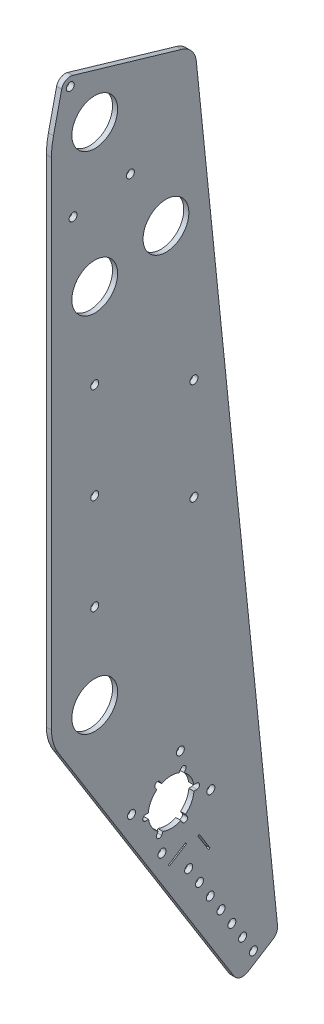
SolidWorks part; units mm, degrees
ref_plane "Front Plane" through (0, 0, 0) normal (0, 0, 1) x (1, 0, 0)
ref_plane "Top Plane" through (0, 0, 0) normal (0, 1, 0) x (1, 0, 0)
ref_plane "Right Plane" through (0, 0, 0) normal (1, 0, 0) x (0, 0, -1)
ref_plane "Plane1" through (1.5875, 0, 0) normal (1, 0, 0) x (0, 0, -1)
sketch "Sketch1" plane through (1.5875, 0, 0) normal (1, 0, 0) x (0, 0, -1)
  line L0 (40.6958, -376.82) -> (41.6603, -378.3635)
  line L1 (52.8023, -377.9745) -> (53.6568, -376.3674)
  line L2 (56.7471, -378.0106) -> (55.8926, -379.6176)
  line L3 (61.8006, -389.0724) -> (63.6196, -389.0088)
  line L4 (63.7417, -392.5067) -> (61.9227, -392.5702)
  line L5 (56.6887, -402.4141) -> (57.6532, -403.9576)
  line L6 (54.685, -405.8123) -> (53.7205, -404.2688)
  line L7 (42.5785, -404.6579) -> (41.724, -406.2649)
  line L8 (38.6337, -404.6217) -> (39.4882, -403.0147)
  line L9 (33.5802, -393.56) -> (31.7612, -393.6235)
  line L10 (31.6391, -390.1256) -> (33.458, -390.0621)
  line L11 (38.6921, -380.2183) -> (37.7276, -378.6748)
  line L12 (45.9843, -424.5347) -> (56.7545, -417.8047)
  line L13 (56.7545, -417.8047) -> (57.2844, -418.6528)
  line L14 (57.2844, -418.6528) -> (46.5142, -425.3827)
  line L15 (46.5142, -425.3827) -> (45.9843, -424.5347)
  line L16 (65.2001, -417.4504) -> (71.93, -428.2206)
  line L17 (71.93, -428.2206) -> (71.082, -428.7505)
  line L18 (71.082, -428.7505) -> (64.352, -417.9803)
  line L19 (64.352, -417.9803) -> (65.2001, -417.4504)
  line L20 (54.3454, 12.1946) -> (-13.7189, 32.1437)
  line L21 (-20.63, 28.0802) -> (-25.7335, 5.5386)
  line L22 (-26.9875, -5.6788) -> (-26.9875, -314.9956)
  line L23 (-22.8867, -329.2968) -> (86.8926, -504.9805)
  line L24 (95.6427, -507.0006) -> (111.1338, -497.3207)
  line L25 (114.0855, -491.2857) -> (63.4067, 1.307)
  circle A0 centre (0, -261.9478) radius 2.5
  circle A1 centre (0, -141.9478) radius 2.5
  circle A2 centre (22.2306, -39.1229) radius 2.5
  circle A3 centre (-13.4937, -44.45) radius 2.5
  arc A4 (37.7276, -378.6748) -> (40.6958, -376.82) centre (39.2117, -377.7474) cw
  arc A5 (41.6603, -378.3635) -> (52.8023, -377.9745) centre (47.6904, -391.3162) cw
  arc A6 (53.6568, -376.3674) -> (56.7471, -378.0106) centre (55.2019, -377.189) cw
  arc A7 (55.8926, -379.6176) -> (61.8006, -389.0724) centre (47.6904, -391.3162) cw
  arc A8 (63.6196, -389.0088) -> (63.7417, -392.5067) centre (63.6806, -390.7578) cw
  arc A9 (61.9227, -392.5702) -> (56.6887, -402.4141) centre (47.6904, -391.3162) cw
  arc A10 (57.6532, -403.9576) -> (54.685, -405.8123) centre (56.1691, -404.8849) cw
  arc A11 (53.7205, -404.2688) -> (42.5785, -404.6579) centre (47.6904, -391.3162) cw
  arc A12 (41.724, -406.2649) -> (38.6337, -404.6217) centre (40.1788, -405.4433) cw
  arc A13 (39.4882, -403.0147) -> (33.5802, -393.56) centre (47.6904, -391.3162) cw
  arc A14 (31.7612, -393.6235) -> (31.6391, -390.1256) centre (31.7001, -391.8746) cw
  arc A15 (33.458, -390.0621) -> (38.6921, -380.2183) centre (47.6904, -391.3162) cw
  circle A16 centre (41.9766, -416.0652) radius 2.5
  circle A17 centre (72.4394, -397.0299) radius 2.5
  circle A18 centre (53.4041, -366.5672) radius 2.5
  circle A19 centre (22.9414, -385.6024) radius 2.5
  circle A20 centre (0, -201.9478) radius 2.5
  circle A21 centre (61.9125, -233.6978) radius 2.5
  circle A22 centre (61.9125, -170.1978) radius 2.5
  circle A23 centre (0, 0) radius 14.2875
  circle A24 centre (0, -88.9) radius 14.2875
  circle A25 centre (0, -314.9956) radius 14.2875
  circle A26 centre (44.4613, -78.2458) radius 14.2875
  circle A27 centre (58.6293, -432.788) radius 2.5
  circle A28 centre (65.3593, -443.5582) radius 2.5
  circle A29 centre (72.0892, -454.3284) radius 2.5
  circle A30 centre (78.8192, -465.0986) radius 2.5
  circle A31 centre (85.5492, -475.8688) radius 2.5
  circle A32 centre (92.2792, -486.639) radius 2.5
  circle A33 centre (99.0091, -497.4092) radius 2.5
  circle A34 centre (-15.2658, 26.8657) radius 2.5
  arc A35 (63.4067, 1.307) -> (54.3454, 12.1946) centre (50.7734, 0.0072) ccw
  arc A36 (-13.7189, 32.1437) -> (-20.63, 28.0802) centre (-15.2658, 26.8657) ccw
  arc A37 (-25.7335, 5.5386) -> (-26.9875, -5.6788) centre (23.8125, -5.6788) ccw
  arc A38 (-26.9875, -314.9956) -> (-22.8867, -329.2968) centre (0, -314.9956) ccw
  arc A39 (86.8926, -504.9805) -> (95.6427, -507.0006) centre (92.2778, -501.6155) ccw
  arc A40 (111.1338, -497.3207) -> (114.0855, -491.2857) centre (107.7689, -491.9355) ccw
extrude "Boss-Extrude1" add sketch "Sketch1" against normal blind 3.175
